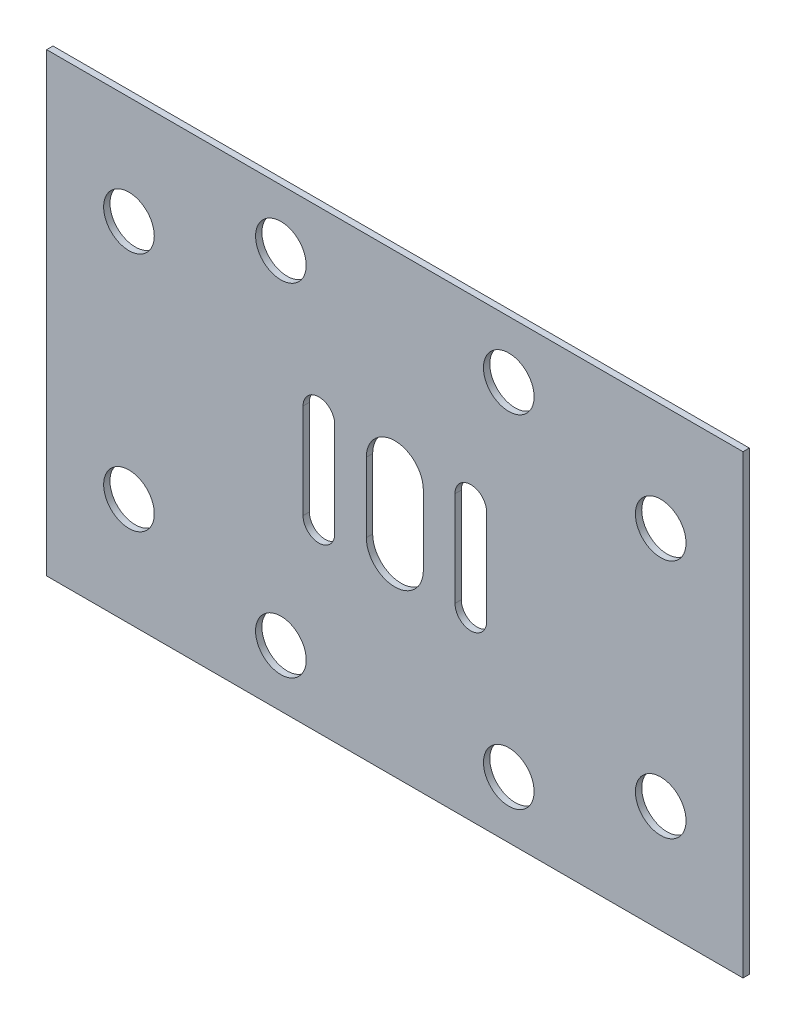
SolidWorks part; units mm, degrees
material "201 Annealed Stainless Steel (SS)"
ref_plane "Front Plane" through (0, 0, 0) normal (0, 0, 1) x (1, 0, 0)
ref_plane "Top Plane" through (0, 0, 0) normal (0, 1, 0) x (1, 0, 0)
ref_plane "Right Plane" through (0, 0, 0) normal (1, 0, 0) x (0, 0, -1)
sketch "Sketch1" plane through (0, 0, 0) normal (0, 0, 1) x (1, 0, 0)
  line L0 (0, 2.75) -> (0, -2.75) construction
  line L1 (2.25, 2.75) -> (2.25, -2.75)
  line L2 (-2.25, 2.75) -> (-2.25, -2.75)
  line L3 (-6, 3.75) -> (-6, -3.75) construction
  line L4 (-4.75, 3.75) -> (-4.75, -3.75)
  line L5 (-7.25, 3.75) -> (-7.25, -3.75)
  line L6 (0, 5) -> (-31.0356, 5) construction
  line L7 (0, -5) -> (-31.0356, -5) construction
  line L8 (0, 0) -> (50000, 0) construction
  line L11 (0, 0) -> (0, -50000) construction
  line L12 (6, 3.75) -> (6, -3.75) construction
  line L13 (-27.5, 18) -> (27.5, 18)
  line L14 (-27.5, 18) -> (-27.5, -18)
  line L15 (-27.5, -18) -> (27.5, -18)
  line L16 (27.5, 18) -> (27.5, -18)
  line L17 (-27.5, 18) -> (27.5, -18) construction
  line L18 (-27.5, -18) -> (27.5, 18) construction
  line L19 (4.75, 3.75) -> (4.75, -3.75)
  line L20 (7.25, 3.75) -> (7.25, -3.75)
  circle A0 centre (-9, 13.5) radius 2
  circle A1 centre (-21, 9.5) radius 2
  arc A8 (2.25, 2.75) -> (-2.25, 2.75) centre (0, 2.75) ccw
  arc A9 (-2.25, -2.75) -> (2.25, -2.75) centre (0, -2.75) ccw
  arc A10 (-4.75, 3.75) -> (-7.25, 3.75) centre (-6, 3.75) ccw
  arc A11 (-7.25, -3.75) -> (-4.75, -3.75) centre (-6, -3.75) ccw
  circle A14 centre (-9, -13.5) radius 2
  circle A15 centre (-21, -9.5) radius 2
  arc A16 (4.75, 3.75) -> (7.25, 3.75) centre (6, 3.75) cw
  arc A17 (7.25, -3.75) -> (4.75, -3.75) centre (6, -3.75) cw
  circle A18 centre (9, -13.5) radius 2
  circle A19 centre (21, -9.5) radius 2
  circle A20 centre (9, 13.5) radius 2
  circle A21 centre (21, 9.5) radius 2
  point P4 (0, 0)
  point P6 (0, 0)
  point P25 (-6, 0)
  point P35 (6, 0)
  dimension "D1" = 4
  dimension "D2" = 10
  dimension "D3" = 2.5
  dimension "D4" = 2.5
  dimension "D5" = 4.5
  dimension "D6" = 55
  dimension "D7" = 36
  dimension "D8" = 9.5
  dimension "D9" = 13.5
  dimension "D10" = 9
  dimension "D11" = 21
extrude "Boss-Extrude1" add sketch "Sketch1" along normal mid plane 0.5
